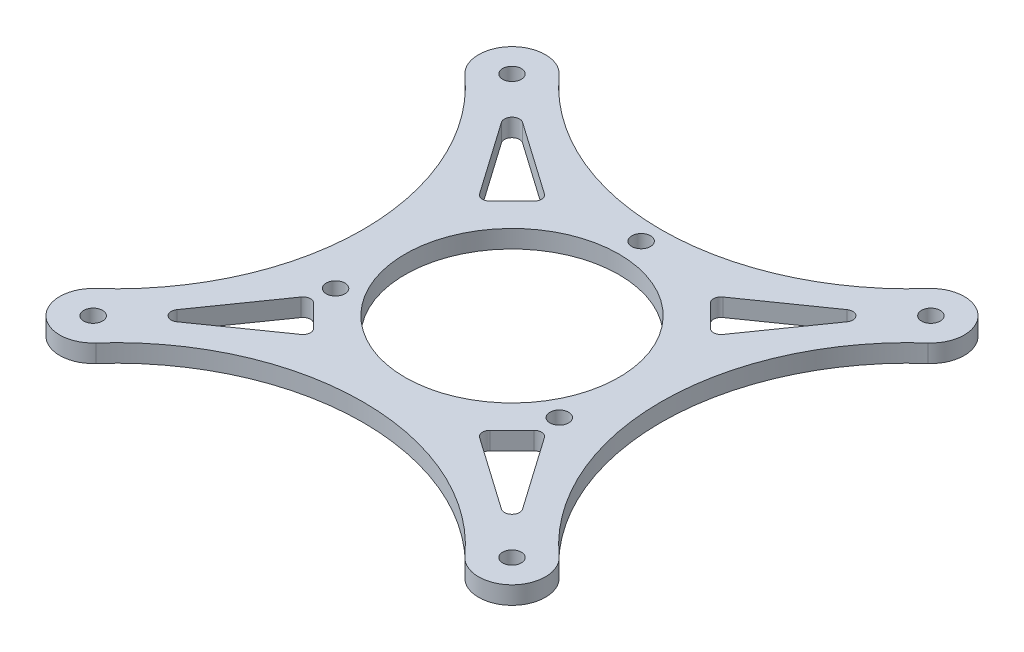
SolidWorks part; units mm, degrees
material "Hexcel AS4C (3000 丝)"
ref_plane "前视基准面" through (0, 0, 0) normal (0, 0, 1) x (1, 0, 0)
ref_plane "上视基准面" through (0, 0, 0) normal (0, 1, 0) x (1, 0, 0)
ref_plane "右视基准面" through (0, 0, 0) normal (1, 0, 0) x (0, 0, -1)
sketch "草图1" plane through (0, 0, 0) normal (0, 1, 0) x (1, 0, 0)
  line L0 (0, 0) -> (0, 29) construction
  line L1 (0, 0) -> (66.5, 0) construction
  line L2 (0, 0) -> (47.0226, 47.0226) construction
  circle A0 centre (0, 0) radius 29 construction
  circle A1 centre (0, 29) radius 2.1
  circle A2 centre (25.1147, -14.5) radius 2.1
  circle A3 centre (-25.1147, -14.5) radius 2.1
  circle A4 centre (0, 0) radius 66.5 construction
  circle A5 centre (47.0226, 47.0226) radius 2.1
  circle A6 centre (47.0226, -47.0226) radius 2.1
  circle A7 centre (-47.0226, -47.0226) radius 2.1
  circle A8 centre (-47.0226, 47.0226) radius 2.1
  circle A9 centre (0, 0) radius 15
  circle A10 centre (0, 0) radius 33.5 construction
  arc A11 (-41.4287, 52.0184) -> (-52.0184, 41.4287) centre (-47.0226, 47.0226) ccw
  arc A12 (41.4287, 52.0184) -> (52.0184, 41.4287) centre (47.0226, 47.0226) cw
  arc A13 (41.4287, -52.0184) -> (52.0184, -41.4287) centre (47.0226, -47.0226) ccw
  arc A14 (-41.4287, -52.0184) -> (-52.0184, -41.4287) centre (-47.0226, -47.0226) cw
  arc A15 (-52.0184, -41.4287) -> (-52.0184, 41.4287) centre (-89.0174, 0) ccw
  arc A16 (52.0184, -41.4287) -> (52.0184, 41.4287) centre (89.0174, 0) cw
  arc A17 (-41.4287, 52.0184) -> (41.4287, 52.0184) centre (0, 89.0174) ccw
  arc A18 (-41.4287, -52.0184) -> (41.4287, -52.0184) centre (0, -89.0174) cw
  point P11 (0, 0)
  dimension "D1" = 58
  dimension "D2" = 4.2
  dimension "D4" = 133
  dimension "D6" = 4.2
  dimension "D7" = 30
  dimension "D8" = 67
  dimension "D9" = 15
  dimension "D5" = 45
  dimension "D3" = 3
extrude "凸台-拉伸1" add sketch "草图1" along normal blind 4
sketch "草图2" plane through (0, 0, 0) normal (0, -1, 0) x (1, 0, 0)
  line L0 (0, 0) -> (11.4715, 16.383) construction
  line L1 (19.0743, 6.0141) -> (0, 0) construction
  line L2 (-0.8724, 19.981) -> (0, 0) construction
  line L3 (0, 0) -> (15, 0) construction
  circle A0 centre (0, 0) radius 20 construction
  arc A1 (-0.8724, 19.981) -> (19.0743, 6.0141) centre (0, 0) cw construction
  arc A2 (23.8429, 7.5176) -> (-1.0905, 24.9762) centre (0, 0) ccw
  arc A3 (14.3058, 4.5106) -> (-0.6543, 14.9857) centre (0, 0) ccw
  arc A4 (14.3058, 4.5106) -> (23.8429, 7.5176) centre (19.0743, 6.0141) ccw
  arc A5 (-1.0905, 24.9762) -> (-0.6543, 14.9857) centre (-0.8724, 19.981) ccw
  arc A6 (17.7402, -9.235) -> (-4.3288, -19.5259) centre (0, 0) cw construction
  arc A7 (-5.411, -24.4074) -> (22.1753, -11.5437) centre (0, 0) ccw
  arc A8 (-3.2466, -14.6444) -> (13.3052, -6.9262) centre (0, 0) ccw
  arc A9 (-3.2466, -14.6444) -> (-5.411, -24.4074) centre (-4.3288, -19.5259) ccw
  arc A10 (22.1753, -11.5437) -> (13.3052, -6.9262) centre (17.7402, -9.235) ccw
  arc A11 (-16.8678, -10.746) -> (-14.7455, 13.5118) centre (0, 0) cw construction
  arc A12 (-18.4319, 16.8898) -> (-21.0848, -13.4325) centre (0, 0) ccw
  arc A13 (-11.0592, 10.1339) -> (-12.6509, -8.0595) centre (0, 0) ccw
  arc A14 (-11.0592, 10.1339) -> (-18.4319, 16.8898) centre (-14.7455, 13.5118) ccw
  arc A15 (-21.0848, -13.4325) -> (-12.6509, -8.0595) centre (-16.8678, -10.746) ccw
  circle A16 centre (0, 0) radius 15 construction
  point P6 (11.4715, 16.383)
  point P20 (8.4524, -18.1262)
  point P27 (-19.9239, 1.7431)
  point P32 (0, 0)
  dimension "D1" = 40
  dimension "D2" = 5
  dimension "D3" = 75
  dimension "D5" = 55
  dimension "D4" = 3
extrude "切除-拉伸1" [suppressed] cut sketch "草图2" against normal through all
sketch "草图3" plane through (0, 0, 0) normal (0, -1, 0) x (1, 0, 0)
  circle A1 centre (0, 0) radius 24
  dimension "D1" = 48
extrude "切除-拉伸2" cut sketch "草图3" against normal through all
sketch "草图4" plane through (0, 0, 0) normal (0, -1, 0) x (1, 0, 0)
  line L0 (0, 0) -> (-47.0226, 47.0226) construction
  line L1 (-44.33, 44.33) -> (-26.163, 18.3848)
  line L2 (-26.163, 18.3848) -> (-18.3848, 26.163)
  line L3 (-18.3848, 26.163) -> (-44.33, 44.33)
  line L4 (26.163, 18.3848) -> (44.33, 44.33)
  line L5 (44.33, 44.33) -> (18.3848, 26.163)
  line L6 (18.3848, 26.163) -> (26.163, 18.3848)
  line L7 (18.3848, -26.163) -> (44.33, -44.33)
  line L8 (44.33, -44.33) -> (26.163, -18.3848)
  line L9 (26.163, -18.3848) -> (18.3848, -26.163)
  line L10 (-26.163, -18.3848) -> (-44.33, -44.33)
  line L11 (-44.33, -44.33) -> (-18.3848, -26.163)
  line L12 (-18.3848, -26.163) -> (-26.163, -18.3848)
  circle A0 centre (0, 0) radius 29 construction
  point P21 (0, 0)
  dimension "D1" = 20
  dimension "D2" = 35
  dimension "D3" = 11
  dimension "D4" = 4
extrude "切除-拉伸3" cut sketch "草图4" against normal through all
fillet "圆角1" radius 1.7 12 edges at (-26.163, 2, 18.3848) (26.163, 2, 18.3848) (18.3848, 2, 26.163) (44.33, 2, 44.33) (18.3848, 2, -26.163) (26.163, 2, -18.3848) (44.33, 2, -44.33) (-26.163, 2, -18.3848) (-18.3848, 2, -26.163) (-44.33, 2, -44.33) (-18.3848, 2, 26.163) (-44.33, 2, 44.33)
